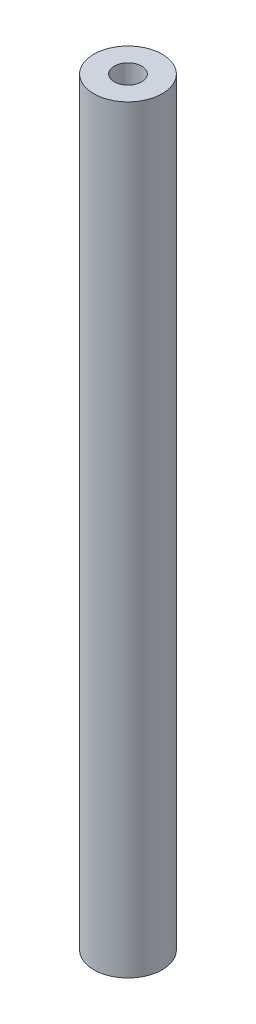
SolidWorks part; units mm, degrees
ref_plane "前视基准面" through (0, 0, 0) normal (0, 0, 1) x (1, 0, 0)
ref_plane "上视基准面" through (0, 0, 0) normal (0, 1, 0) x (1, 0, 0)
ref_plane "右视基准面" through (0, 0, 0) normal (1, 0, 0) x (0, 0, -1)
other "Configuration Table"
sketch "草图1" plane through (0, 0, 0) normal (0, 1, 0) x (1, 0, 0)
  circle A0 centre (0, 0) radius 2.5
  circle A1 centre (0, 0) radius 1
  dimension "D1" = 2
  dimension "D2" = 5
extrude "凸台-拉伸1" add sketch "草图1" along normal blind 55.4
